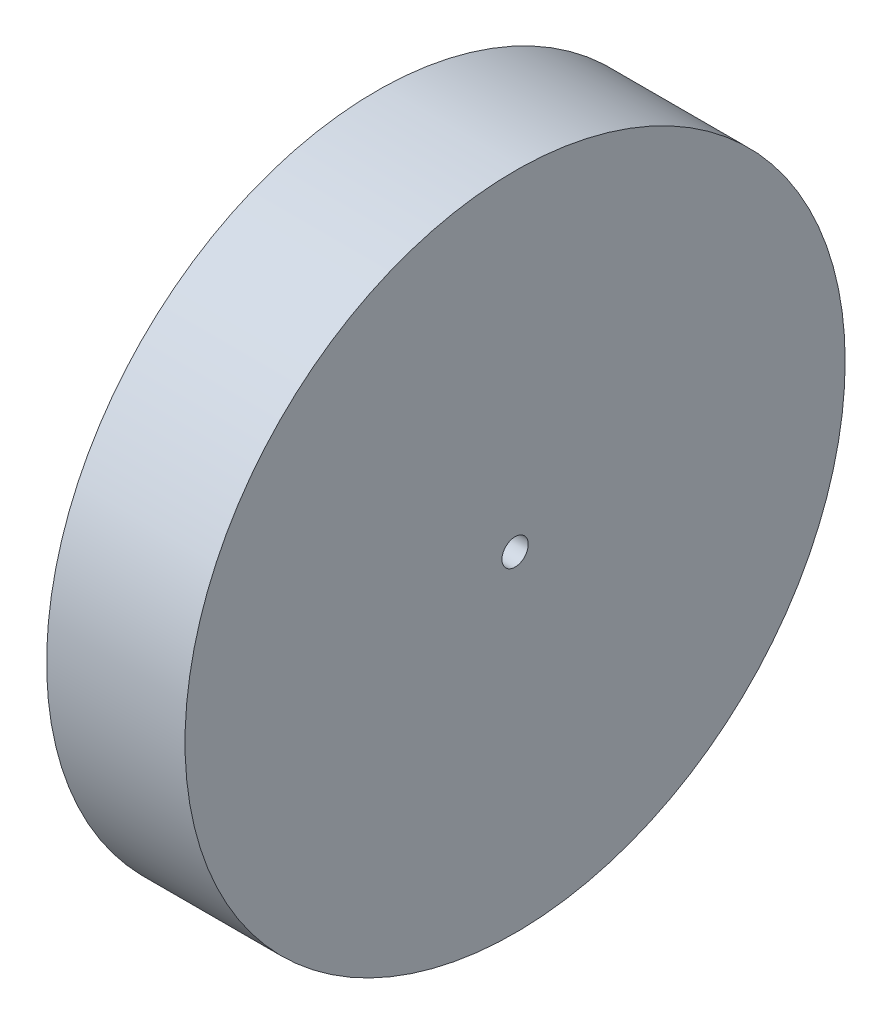
SolidWorks part; units mm, degrees
ref_plane "Alzado" through (0, 0, 0) normal (0, 0, 1) x (1, 0, 0)
ref_plane "Planta" through (0, 0, 0) normal (0, 1, 0) x (1, 0, 0)
ref_plane "Vista lateral" through (0, 0, 0) normal (1, 0, 0) x (0, 0, -1)
sketch "Croquis1" plane through (0, 0, 0) normal (1, 0, 0) x (0, 0, -1)
  circle A0 centre (0, 0) radius 288.6
  dimension "D1" = 577.2
extrude "Saliente-Extruir1" add sketch "Croquis1" along normal blind 121
sketch "Croquis2" plane through (0, 0, 0) normal (-1, 0, 0) x (0, 0, 1)
  line L0 (0, 288.6) -> (0, -288.6) construction
  line L1 (-288.6, 0) -> (288.6, 0) construction
  circle A0 centre (0, 0) radius 11.5
  circle A1 centre (0, 0) radius 288.6 construction
  point P16 (0, 0)
  point P43 (0, 0)
  dimension "D1" = 23
extrude "Cortar-Extruir1" cut sketch "Croquis2" against normal through all
equation "\"DiamTubo\" = 457.2 + 120"
equation "\"D1@Croquis1\"=\"DiamTubo\""
